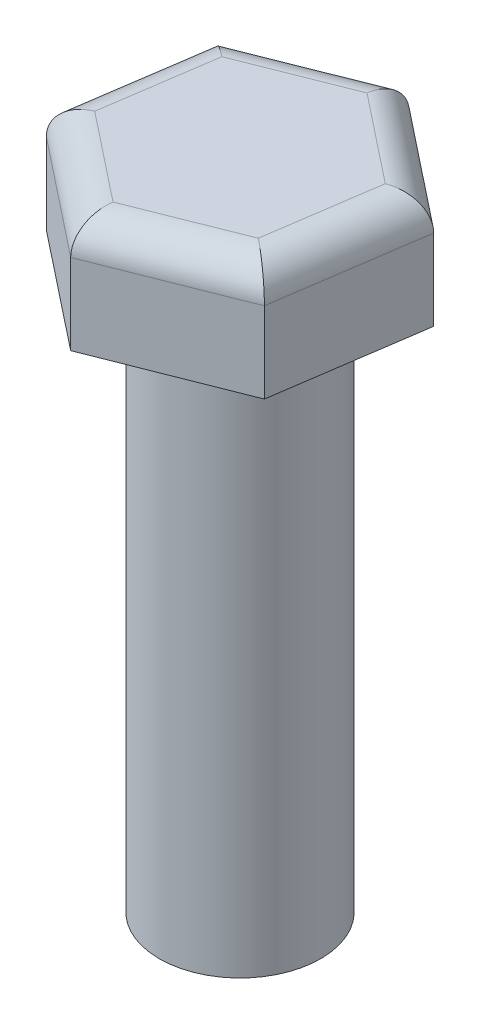
SolidWorks part; units mm, degrees
ref_plane "Спереди" through (0, 0, 0) normal (0, 0, 1) x (1, 0, 0)
ref_plane "Сверху" through (0, 0, 0) normal (0, 1, 0) x (1, 0, 0)
ref_plane "Справа" through (0, 0, 0) normal (1, 0, 0) x (0, 0, -1)
sketch "Эскиз1" plane through (0, 0, 0) normal (0, 1, 0) x (1, 0, 0)
  circle A0 centre (0, 0) radius 2.5
extrude "Вытянуть1" add sketch "Эскиз1" along normal blind 17
sketch "Эскиз2" plane through (0, 17, 0) normal (0, 1, 0) x (1, 0, 0)
  line L1 (3.6214, -2.8668) -> (4.2934, 1.7029)
  line L2 (4.2934, 1.7029) -> (0.672, 4.5697)
  line L3 (0.672, 4.5697) -> (-3.6214, 2.8668)
  line L4 (-3.6214, 2.8668) -> (-4.2934, -1.7029)
  line L5 (-4.2934, -1.7029) -> (-0.672, -4.5697)
  line L6 (-0.672, -4.5697) -> (3.6214, -2.8668)
  circle A0 centre (0, 0) radius 4 construction
  dimension "D1" = 8
extrude "Вытянуть2" add sketch "Эскиз2" along normal blind 3.5
fillet "Скругление1" radius 1 6 edges at (1.4747, 20.5, 3.7182) (3.9574, 20.5, 0.582) (2.4827, 20.5, -3.1363) (-1.4747, 20.5, -3.7182) (-3.9574, 20.5, -0.582) (-2.4827, 20.5, 3.1363)
